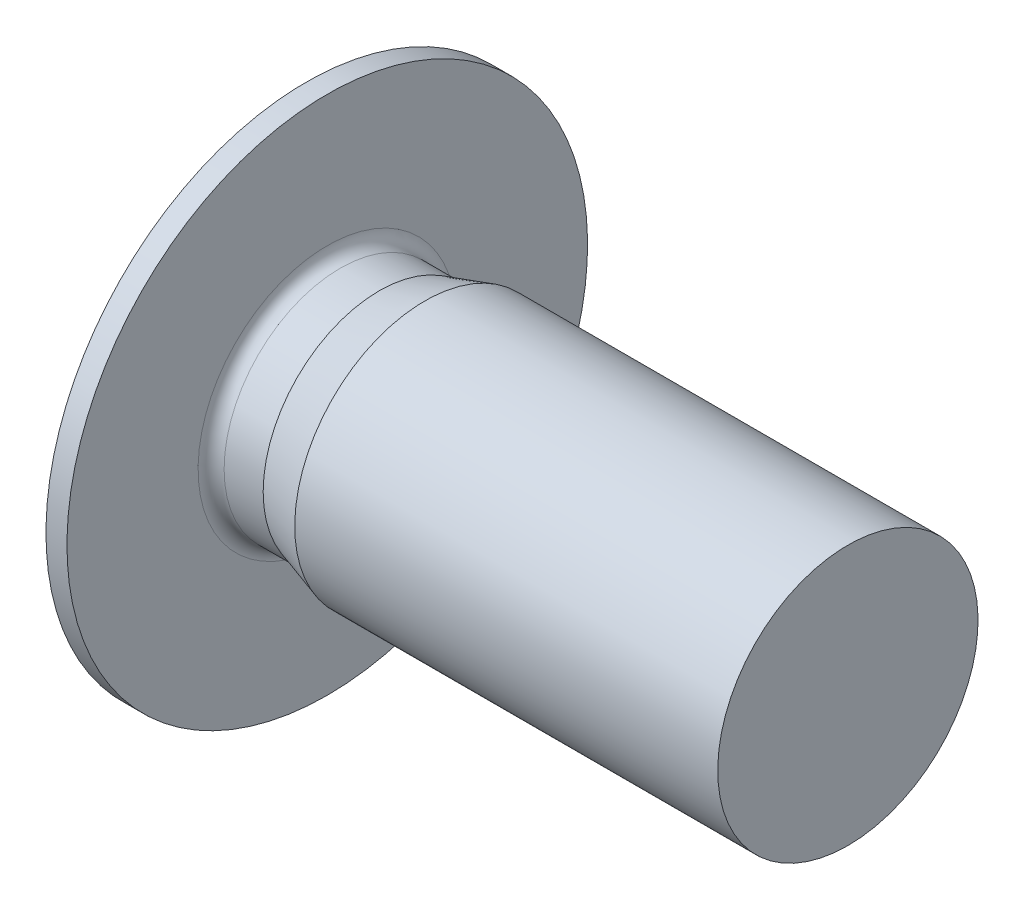
SolidWorks part; units mm, degrees
material "SUS304相当"
ref_plane "Front Plane" through (0, 0, 0) normal (0, 0, 1) x (1, 0, 0)
ref_plane "Top Plane" through (0, 0, 0) normal (0, 1, 0) x (1, 0, 0)
ref_plane "Right Plane" through (0, 0, 0) normal (1, 0, 0) x (0, 0, -1)
sketch "Sketch1" plane through (0, 0, 0) normal (0, 0, 1) x (1, 0, 0)
  line L0 (-0.9, 0) -> (8, 0) construction
  line L1 (-0.9, 0) -> (-0.9, 3)
  line L2 (-0.3226, 4) -> (0, 4)
  line L3 (0, 4) -> (0, 1.785)
  line L4 (1.5, 2) -> (8, 2)
  line L5 (8, 2) -> (8, 0)
  line L6 (8, 0) -> (-0.9, 0)
  line L7 (1.5, 2) -> (0.8, 1.785)
  line L8 (0.8, 1.785) -> (0, 1.785)
  line L9 (-0.3226, 4) -> (-0.9, 3)
  line L10 (-0.9, 0) -> (8, 0) construction
  dimension "A" = 8
  dimension "M" = 4
  dimension "L" = 8
  dimension "E" = 0.9
  dimension "FIX_1" = 30
  dimension "MSM_1" = 6
  dimension "MSM_2" = 3.57
  dimension "MSM_3" = 0.7
  dimension "E_s" = 1.5
revolve "Revolve1" add sketch "Sketch1" angle 360 about L0
cosmetic thread "Thread1" parameters "ATL_1"=6.5, "ATD"=3.242
fillet "Fillet1" radius 0.2 1 edges at (0, -1.785, 0)
sketch "Sketch2" plane through (-0.9, 0, 0) normal (-1, 0, 0) x (0, 0, 1)
  line L1 (0, 1.1547) -> (-1, 0.5774)
  line L2 (-1, 0.5774) -> (-1, -0.5774)
  line L3 (-1, -0.5774) -> (0, -1.1547)
  line L4 (0, -1.1547) -> (1, -0.5774)
  line L5 (1, -0.5774) -> (1, 0.5774)
  line L6 (1, 0.5774) -> (0, 1.1547)
  circle A0 centre (0, 0) radius 1 construction
  dimension "B" = 2
extrude "Cut-Extrude1" cut sketch "Sketch2" against normal blind 2.5
sketch "Sketch3" plane through (0, 0, 0) normal (0, 0, 1) x (1, 0, 0)
  line L0 (1.6, 0) -> (2.2009, 0) construction
  line L1 (1.6, 0) -> (1.6, 1)
  line L2 (1.6, 1) -> (2.2009, 0)
  line L3 (2.2009, 0) -> (1.6, 0)
  line L5 (1.6, 0.5774) -> (1.6, -0.5774) construction
  dimension "FIX_3" = 59
  dimension "B" = 2
revolve "Cut-Revolve1" cut sketch "Sketch3" angle 360 about L0
equation "\"ATL_1@Thread1\" = \"L@Sketch1\" - \"E_s@Sketch1\""
